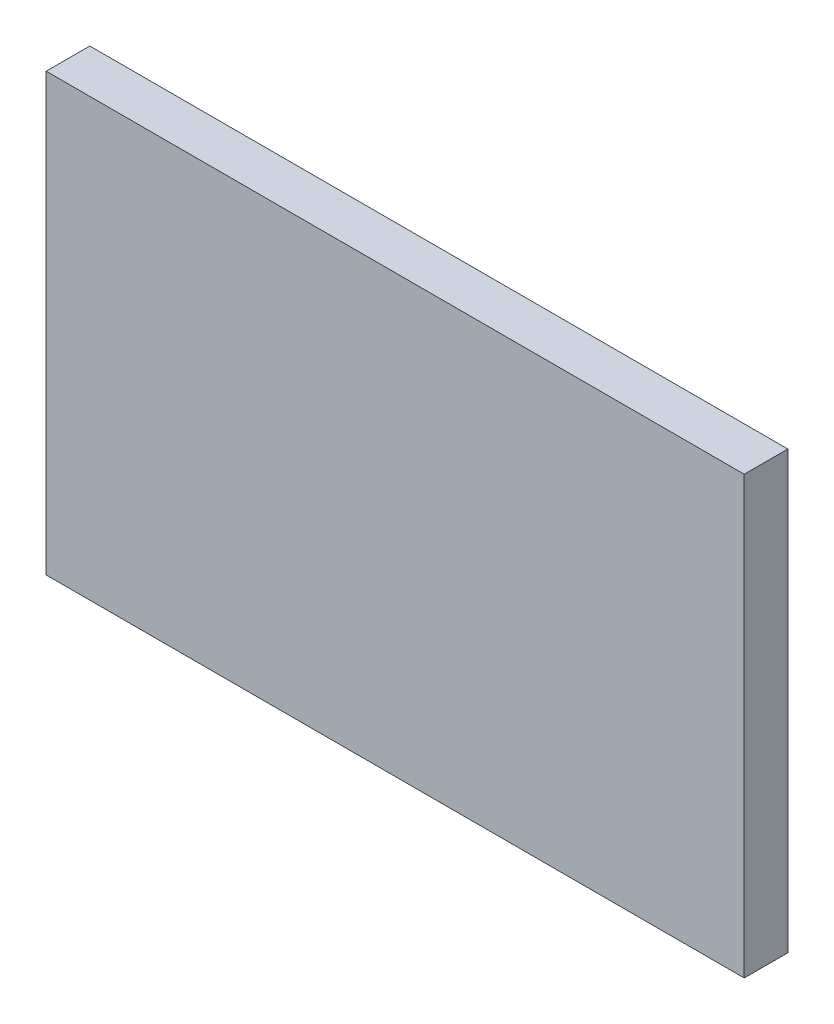
SolidWorks part; units mm, degrees
ref_plane "Plan de face" through (0, 0, 0) normal (0, 0, 1) x (1, 0, 0)
ref_plane "Plan de dessus" through (0, 0, 0) normal (0, 1, 0) x (1, 0, 0)
ref_plane "Plan de droite" through (0, 0, 0) normal (1, 0, 0) x (0, 0, -1)
sketch "Esquisse1" plane through (0, 0, 0) normal (0, 0, 1) x (1, 0, 0)
  line L1 (-39.0191, 29.7539) -> (120.9809, 29.7539)
  line L2 (-39.0191, 29.7539) -> (-39.0191, -70.2461)
  line L3 (-39.0191, -70.2461) -> (120.9809, -70.2461)
  line L4 (120.9809, 29.7539) -> (120.9809, -70.2461)
  dimension "D1" = 160
  dimension "D2" = 100
extrude "Boss.-Extru.1" add sketch "Esquisse1" along normal blind 10
